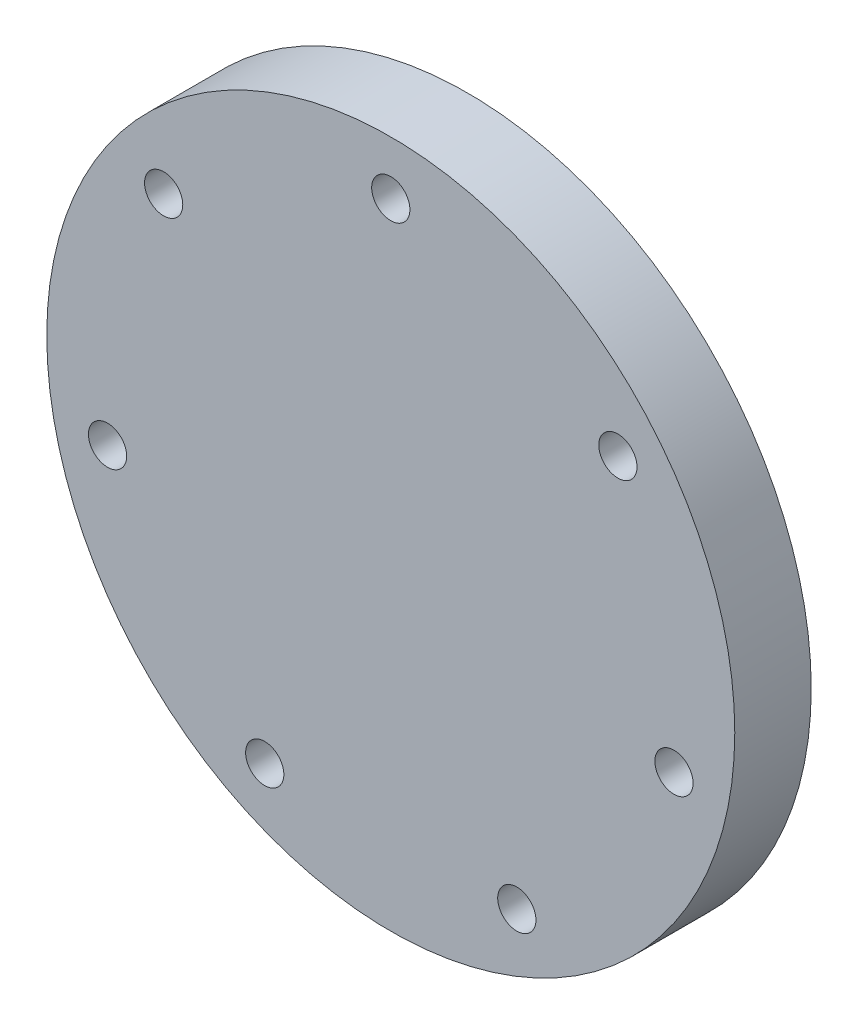
SolidWorks part; units mm, degrees
ref_plane "Front Plane" through (0, 0, 0) normal (0, 0, 1) x (1, 0, 0)
ref_plane "Top Plane" through (0, 0, 0) normal (0, 1, 0) x (1, 0, 0)
ref_plane "Right Plane" through (0, 0, 0) normal (1, 0, 0) x (0, 0, -1)
sketch "Sketch1" plane through (0, 0, 0) normal (0, 0, 1) x (1, 0, 0)
  line L0 (0, 0) -> (0, 19) construction
  circle A0 centre (0, 0) radius 22.5
  circle A1 centre (0, 0) radius 19 construction
  circle A2 centre (0, 19) radius 1.25
  circle A3 centre (14.8548, 11.8463) radius 1.25
  circle A4 centre (18.5236, -4.2279) radius 1.25
  circle A5 centre (8.2438, -17.1184) radius 1.25
  circle A6 centre (-8.2438, -17.1184) radius 1.25
  circle A7 centre (-18.5236, -4.2279) radius 1.25
  circle A9 centre (-14.8548, 11.8463) radius 1.25
  point P19 (0, 0)
  dimension "D1" = 38
  dimension "D2" = 45
  dimension "D3" = 2.5
  dimension "D4" = 7
extrude "Boss-Extrude1" add sketch "Sketch1" along normal blind 5
